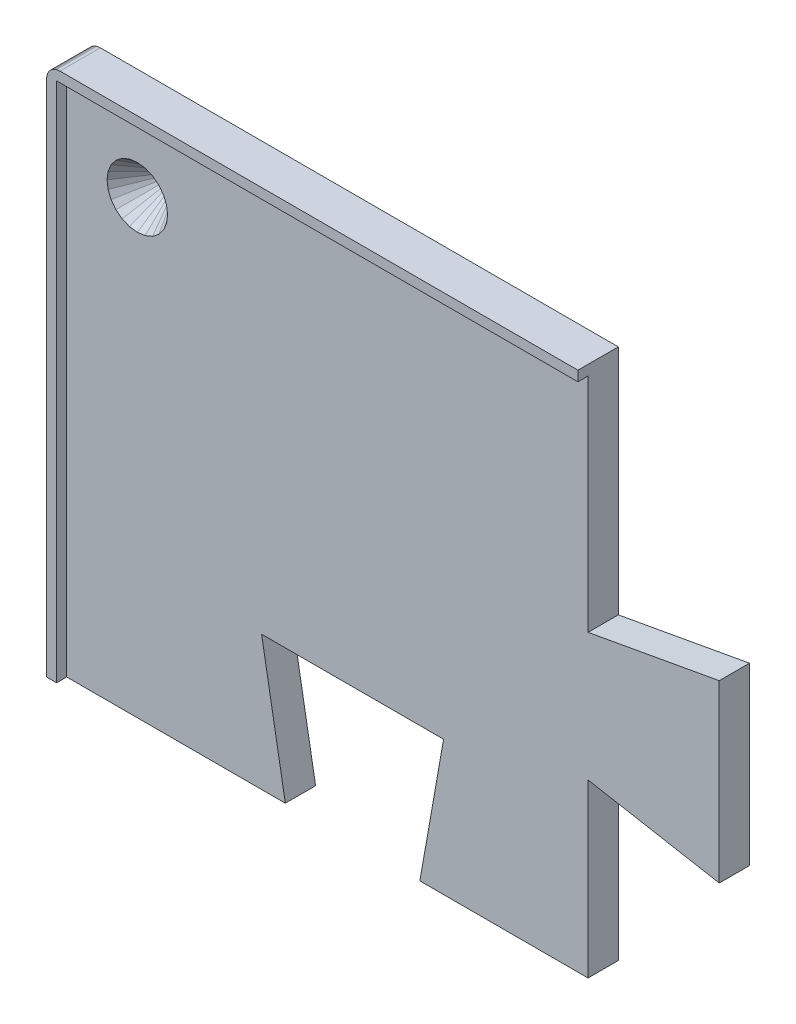
SolidWorks part; units mm, degrees
ref_plane "Front Plane" through (0, 0, 0) normal (0, 0, 1) x (1, 0, 0)
ref_plane "Top Plane" through (0, 0, 0) normal (0, 1, 0) x (1, 0, 0)
ref_plane "Right Plane" through (0, 0, 0) normal (1, 0, 0) x (0, 0, -1)
ref_plane "Plane1" through (0, 0, 9.15) normal (0, 0, 1) x (1, 0, 0)
sketch "Sketch1" plane through (0, 0, 9.15) normal (0, 0, 1) x (1, 0, 0)
  line L0 (-2, 77) -> (77, 77)
  line L1 (77, 77) -> (77, 156)
  line L2 (77, 156) -> (0, 156)
  line L3 (0, 156) -> (-0.5176, 155.9319)
  line L4 (-0.5176, 155.9319) -> (-0.7654, 155.8478)
  line L5 (-0.7654, 155.8478) -> (-1, 155.7321)
  line L6 (-1, 155.7321) -> (-1.2175, 155.5867)
  line L7 (-1.2175, 155.5867) -> (-1.4142, 155.4142)
  line L8 (-1.4142, 155.4142) -> (-1.5867, 155.2175)
  line L9 (-1.5867, 155.2175) -> (-1.7321, 155)
  line L10 (-1.7321, 155) -> (-1.8478, 154.7654)
  line L11 (-1.8478, 154.7654) -> (-1.9319, 154.5176)
  line L12 (-1.9319, 154.5176) -> (-2, 154)
  line L13 (-2, 154) -> (-2, 77)
extrude "Boss-Extrude1" add sketch "Sketch1" against normal blind 6
sketch "Sketch2" plane through (77, 0, 0) normal (1, 0, 0) x (0, 0, -1)
  line L0 (-7.65, 125.0265) -> (-3.15, 125.0265)
  line L1 (-3.15, 125.0265) -> (-3.15, 77)
  line L2 (-3.15, 77) -> (-7.65, 77)
  line L3 (-7.65, 77) -> (-7.65, 125.0265)
extrude "Boss-Extrude2" add sketch "Sketch2" along normal blind 19.5
sketch "Sketch3" plane through (77, 0, 0) normal (1, 0, 0) x (0, 0, -1)
  line L0 (-9.15, 77) -> (-7.65, 77)
  line L1 (-7.65, 77) -> (-7.65, 154.5)
  line L2 (-7.65, 154.5) -> (-9.15, 154.5)
  line L3 (-9.15, 154.5) -> (-9.15, 77)
extrude "Cut-Extrude1" cut sketch "Sketch3" against normal blind 77.5
sketch "Sketch4" plane through (0, 0, 3.15) normal (0, 0, -1) x (-1, 0, 0)
  line L0 (-55.5265, 77) -> (-28.4735, 77)
  line L1 (-28.4735, 77) -> (-28.4735, 97)
  line L2 (-28.4735, 97) -> (-55.5265, 97)
  line L3 (-55.5265, 97) -> (-55.5265, 77)
extrude "Cut-Extrude2" cut sketch "Sketch4" against normal through all
sketch "Sketch5" plane through (0, 0, 3.15) normal (0, 0, -1) x (-1, 0, 0)
  line L0 (-77, 98.9735) -> (-96.5, 98.9735)
  line L1 (-96.5, 98.9735) -> (-96.5, 77)
  line L2 (-96.5, 77) -> (-77, 77)
  line L3 (-77, 77) -> (-77, 98.9735)
extrude "Cut-Extrude3" cut sketch "Sketch5" against normal through all
sketch "Sketch6" plane through (0, 0, 3.15) normal (0, 0, -1) x (-1, 0, 0)
  line L0 (-11.0607, 142.9393) -> (-10.75, 142.701)
  line L1 (-10.75, 142.701) -> (-10.3882, 142.5511)
  line L2 (-10.3882, 142.5511) -> (-10, 142.5)
  line L3 (-10, 142.5) -> (-9.6118, 142.5511)
  line L4 (-9.6118, 142.5511) -> (-9.25, 142.701)
  line L5 (-9.25, 142.701) -> (-8.9393, 142.9393)
  line L6 (-8.9393, 142.9393) -> (-8.701, 143.25)
  line L7 (-8.701, 143.25) -> (-8.5511, 143.6118)
  line L8 (-8.5511, 143.6118) -> (-8.5, 144)
  line L9 (-8.5, 144) -> (-8.5511, 144.3882)
  line L10 (-8.5511, 144.3882) -> (-8.701, 144.75)
  line L11 (-8.701, 144.75) -> (-8.9393, 145.0607)
  line L12 (-8.9393, 145.0607) -> (-9.25, 145.299)
  line L13 (-9.25, 145.299) -> (-9.6118, 145.4489)
  line L14 (-9.6118, 145.4489) -> (-10, 145.5)
  line L15 (-10, 145.5) -> (-10.3882, 145.4489)
  line L16 (-10.3882, 145.4489) -> (-10.75, 145.299)
  line L17 (-10.75, 145.299) -> (-11.0607, 145.0607)
  line L18 (-11.0607, 145.0607) -> (-11.299, 144.75)
  line L19 (-11.299, 144.75) -> (-11.4489, 144.3882)
  line L20 (-11.4489, 144.3882) -> (-11.5, 144)
  line L21 (-11.5, 144) -> (-11.4489, 143.6118)
  line L22 (-11.4489, 143.6118) -> (-11.299, 143.25)
  line L23 (-11.299, 143.25) -> (-11.0607, 142.9393)
extrude "Cut-Extrude4" cut sketch "Sketch6" against normal up to next (4.5 mm away) draft 33.463
draft "Draft1" type of draft neutral plane draft angle 10 faces to draft 2 face at (55.5265, 87, 5.4) face at (28.4735, 87, 5.4) neutral plane through (28.4735, 97, 9.15) neutral plane normal (0, -1, 0) reverse direction yes parameters "D1"=10
draft "Draft2" type of draft neutral plane draft angle 10.251 faces to draft 2 face at (86.75, 98.9735, 5.4) face at (89.1875, 125.0265, 4.8375) neutral plane through (96.5, 0, 0) neutral plane normal (1, 0, 0) reverse direction yes parameters "D1"=10.251
